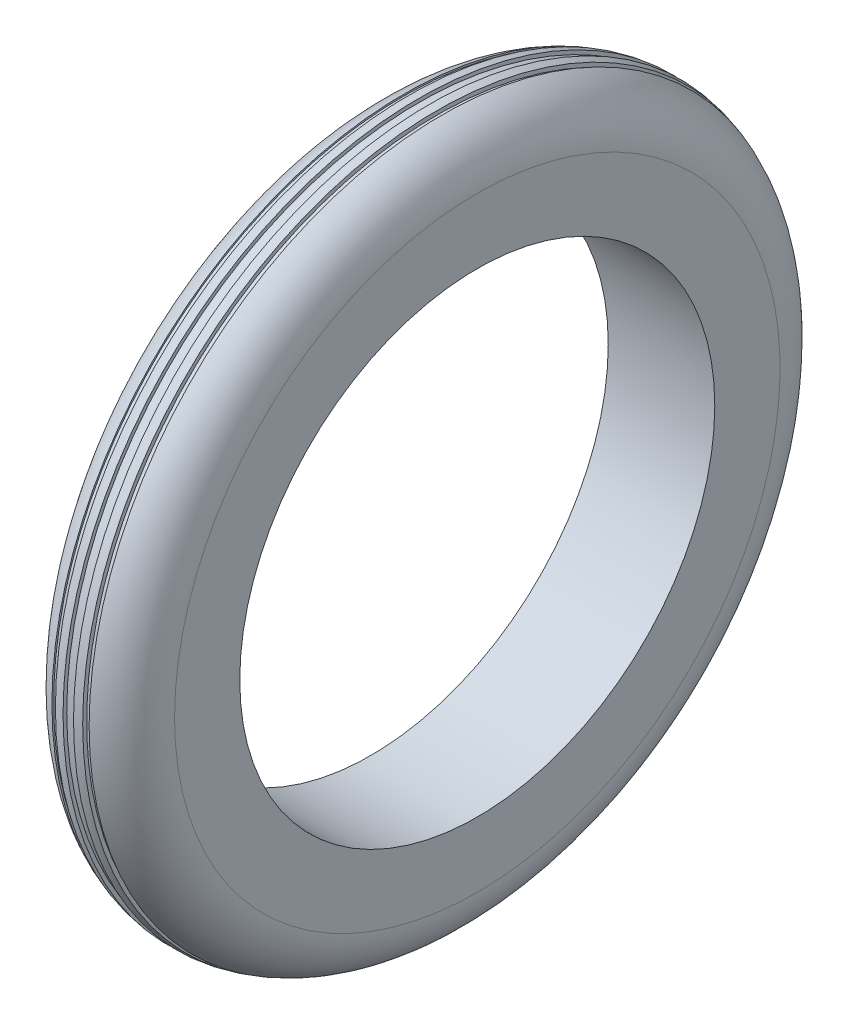
SolidWorks part; units mm, degrees
ref_plane "Front Plane" through (0, 0, 0) normal (0, 0, 1) x (1, 0, 0)
ref_plane "Top Plane" through (0, 0, 0) normal (0, 1, 0) x (1, 0, 0)
ref_plane "Right Plane" through (0, 0, 0) normal (1, 0, 0) x (0, 0, -1)
sketch "Sketch1" plane through (0, 0, 0) normal (0, 0, 1) x (1, 0, 0)
  line L0 (-52.2857, 0) -> (54.6739, 0) construction
  line L2 (-10.0915, 57.357) -> (-10.0915, 45)
  line L3 (-10.0915, 45) -> (10.0915, 45)
  line L4 (10.0915, 57.357) -> (10.0915, 45)
  line L5 (-10.0915, 57.357) -> (10.0915, 45) construction
  line L6 (-10.0915, 45) -> (10.0915, 57.357) construction
  arc A0 (-10.0915, 57.357) -> (10.0915, 57.357) centre (0, 57.357) cw
  point P0 (0, 51.1785)
  dimension "D1" = 45
revolve "Revolve1" add sketch "Sketch1" angle 360 about L0
sketch "Sketch2" plane through (0, 0, 0) normal (0, 0, 1) x (1, 0, 0)
  line L1 (0.9914, 66.7007) -> (-0.9914, 66.7007)
  line L2 (0.9914, 66.7007) -> (0.9914, 70.746)
  line L3 (0.9914, 70.746) -> (-0.9914, 70.746)
  line L4 (-0.9914, 66.7007) -> (-0.9914, 70.746)
  line L5 (0.9914, 66.7007) -> (-0.9914, 70.746) construction
  line L6 (0.9914, 70.746) -> (-0.9914, 66.7007) construction
  line L7 (2.4705, 71.0572) -> (3.404, 71.0572)
  line L8 (2.4705, 71.0572) -> (2.4705, 66.3895)
  line L9 (2.4705, 66.3895) -> (3.404, 66.3895)
  line L10 (3.404, 71.0572) -> (3.404, 66.3895)
  line L11 (2.4705, 71.0572) -> (3.404, 66.3895) construction
  line L12 (2.4705, 66.3895) -> (3.404, 71.0572) construction
  line L13 (-3.7921, 71.0572) -> (-2.7807, 71.0572)
  line L14 (-3.7921, 71.0572) -> (-3.7921, 66.3895)
  line L15 (-3.7921, 66.3895) -> (-2.7807, 66.3895)
  line L16 (-2.7807, 71.0572) -> (-2.7807, 66.3895)
  line L17 (-3.7921, 71.0572) -> (-2.7807, 66.3895) construction
  line L18 (-3.7921, 66.3895) -> (-2.7807, 71.0572) construction
  point P0 (0, 68.7234)
  point P5 (2.9372, 68.7234)
  point P10 (-3.2864, 68.7234)
revolve "Cut-Revolve1" cut sketch "Sketch2" angle 360
